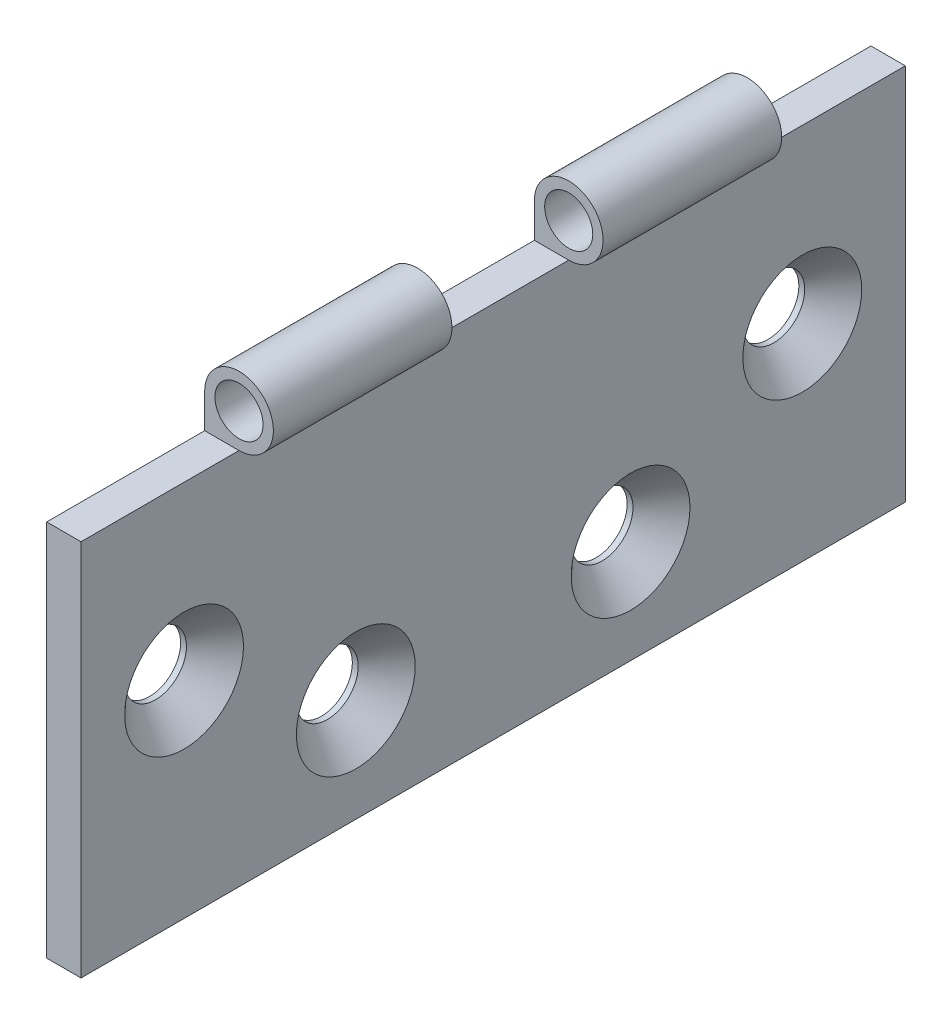
SolidWorks part; units mm, degrees
ref_plane "Front Plane" through (0, 0, 0) normal (0, 0, 1) x (1, 0, 0)
ref_plane "Top Plane" through (0, 0, 0) normal (0, 1, 0) x (1, 0, 0)
ref_plane "Right Plane" through (0, 0, 0) normal (1, 0, 0) x (0, 0, -1)
sketch "Эскиз1" plane through (0, 0, 0) normal (0, 0, 1) x (1, 0, 0)
  line L0 (0, 0) -> (0, 60)
  dimension "D1" = 60
extrude "Вытянуть-Тонкостенный1" add sketch "Эскиз1" along normal mid plane 120 thin
sketch "Эскиз2" plane through (0, 0, 60) normal (0, 0, 1) x (1, 0, 0)
  circle A0 centre (5, 60) radius 5
sweep "По траектории1" add profiles "Эскиз2" path edge at (5, 60, 0)
sketch "Эскиз4" plane through (0, 0, 60) normal (0, 0, 1) x (1, 0, 0)
  circle A0 centre (5, 60) radius 3.5
  arc A1 (5, 55) -> (0, 60) centre (5, 60) ccw construction
extrude "Вырез-Вытянуть1" cut sketch "Эскиз4" against normal through all
hole_wizard "Зенковка для  винта с плоской головкой M81" positions "Эскиз6" profile "Эскиз5" countersink size "M8" standard "Ansi Metric" end condition through all
sketch "Эскиз6" plane through (5, 0, 0) normal (1, 0, 0) x (0, 0, -1)
  point P0 (-45, 30)
  point P2 (-20, 15)
  dimension "D1" = 30
  dimension "D2" = 15
  dimension "D3" = 15
  dimension "D4" = 40
sketch "Эскиз5" plane through (5, 30, 45) normal (0, 1, 0) x (0, 0, -1)
  line L0 (0, 0) -> (0, 5)
  line L1 (0, 5) -> (4.5, 5)
  line L2 (4.5, 5) -> (4.5, 4.15)
  line L3 (4.5, 4.15) -> (8.65, 0)
  line L5 (8.65, 0) -> (0, 0)
  line L6 (-4.5, 4.15) -> (-8.65, 0) construction
  line L11 (0, -6.35) -> (0, 107.95) construction
  dimension "Диаметр сквозного отверстия" = 9
  dimension "Глубина сквозного отверстия" = 5
  dimension "Диаметр передней зенковки" = 17.3
  dimension "Угол передней зенковки" = 90
mirror "Зеркальное отражение1" about plane through (0, 0, 0) normal (0, 0, 1) of "Зенковка для  винта с плоской головкой M81"
sketch "компоновка для вырезов" plane through (5, 0, 0) normal (1, 0, 0) x (0, 0, -1)
  line L5 (-60, 65) -> (-60, 55) construction
  line L6 (60, 54) -> (-60, 54)
  line L7 (60, 54) -> (-60, 54)
  line L8 (60, 55) -> (60, 65) construction
  line L9 (-60, 65) -> (-60, 54)
  line L10 (60, 54) -> (60, 65)
  line L11 (-36, 65) -> (-36, 54)
  line L12 (-12, 65) -> (-12, 54)
  line L13 (60, 65) -> (-60, 65) construction
  line L14 (0, 96.9295) -> (0, 0) construction
  line L15 (12, 65) -> (12, 54)
  line L16 (36, 65) -> (36, 54)
  dimension "D2" = 24
  dimension "D3" = 24
  dimension "D1" = 1
sketch "Эскиз7" plane through (5, 0, 0) normal (1, 0, 0) x (0, 0, -1)
  line L0 (60, 54) -> (60, 65) construction
  line L1 (60, 54) -> (-60, 54) construction
  line L2 (-60, 65) -> (-60, 54) construction
  line L3 (60, 54) -> (60, 65)
  line L4 (60, 0) -> (60, 55)
  line L5 (60, 55) -> (-60, 55)
  line L6 (-60, 55) -> (-60, 0)
  line L7 (-60, 0) -> (60, 0)
  line L8 (60, 0) -> (60, 55)
  line L9 (60, 55) -> (-60, 55)
  line L10 (-60, 55) -> (-60, 0)
  line L11 (-60, 0) -> (60, 0)
  line L12 (60, 54) -> (37, 54)
  line L13 (-60, 65) -> (-60, 54)
  line L14 (60, 65) -> (37, 65)
  line L15 (-37, 65) -> (-60, 65)
  line L16 (-37, 54) -> (-60, 54)
  line L18 (-37, 65) -> (-37, 54)
  line L19 (-37, 65) -> (-37, 54)
  line L20 (11, 65) -> (-11, 65)
  line L21 (-11, 65) -> (-11, 54)
  line L22 (-11, 65) -> (-11, 54)
  line L24 (11, 65) -> (11, 54)
  line L25 (11, 65) -> (11, 54)
  line L26 (11, 54) -> (-11, 54)
  line L27 (37, 65) -> (37, 54)
  line L28 (37, 65) -> (37, 54)
  point P8 (28.8911, 81.2591)
  dimension "D1" = 0
  dimension "D3" = 1
  dimension "D4" = 1
  dimension "D5" = 1
  dimension "D6" = 1
extrude "Вырез-Вытянуть2" cut sketch "Эскиз7" against normal through all both and the other way through all contours L14 L28 L5 L3 | L25 L20 L22 L9 | L19 L15 L13 L9
equation "\"D1@Эскиз6\"= \"D1@Эскиз1\" / 2"
equation "\"D4@Эскиз6\"= \"D1@Вытянуть-Тонкостенный1\" / 3"
equation "\"D2@компоновка для вырезов\"= \"D1@Вытянуть-Тонкостенный1\" / 5"
equation "\"D3@компоновка для вырезов\"= \"D1@Вытянуть-Тонкостенный1\" / 5"
